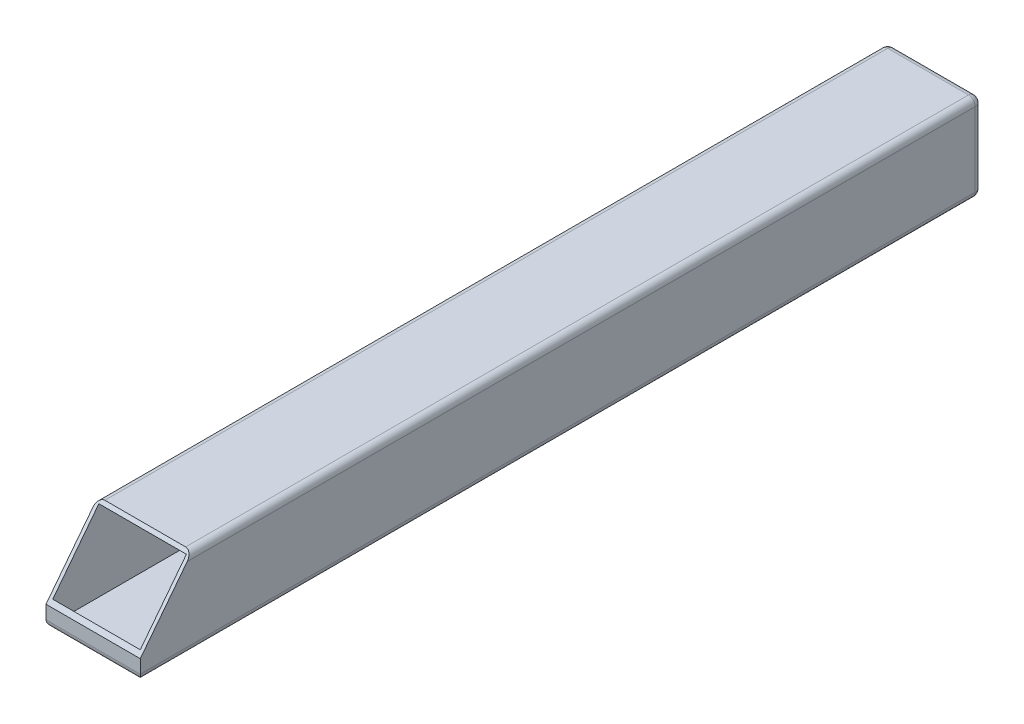
SolidWorks part; units mm, degrees
material "1060 Alloy"
ref_plane "Front Plane" through (0, 0, 0) normal (0, 0, 1) x (1, 0, 0)
ref_plane "Top Plane" through (0, 0, 0) normal (0, 1, 0) x (1, 0, 0)
ref_plane "Right Plane" through (0, 0, 0) normal (1, 0, 0) x (0, 0, -1)
sketch "Sketch1" plane through (0, 0, 0) normal (0, 1, 0) x (1, 0, 0)
  line L1 (0, 0) -> (177.8, 0)
  line L2 (0, 0) -> (0, 1587.5)
  line L3 (0, 1587.5) -> (177.8, 1587.5)
  line L4 (177.8, 0) -> (177.8, 1587.5)
  dimension "D1" = 1587.5
  dimension "D2" = 177.8
extrude "Boss-Extrude1" add sketch "Sketch1" along normal blind 165.1
sketch "Sketch2" plane through (177.8, 0, 0) normal (1, 0, 0) x (0, 0, -1)
  line L0 (0, 165.1) -> (98.3179, 165.1)
  line L1 (0, 165.1) -> (1587.5, 165.1) construction
  line L2 (98.3179, 165.1) -> (0, 38.1)
  line L4 (0, 38.1) -> (0, 165.1)
  line L5 (0, 165.1) -> (0, 0) construction
  point P5 (0, 28.2126)
  point P9 (98.3179, 165.1)
extrude "Cut-Extrude1" cut sketch "Sketch2" against normal up to surface (177.8 mm away) up to face at (0, 82.55, -793.75)
shell "Shell2" thickness 6.35
fillet "Fillet3" radius 12.7 9 edges at (88.9, 0, -1587.5) (88.9, 165.1, -1587.5) (177.8, 82.55, -1587.5) (0, 82.55, -1587.5) (0, 0, -793.75) (177.8, 0, -793.75) (88.9, 0, 0) (0, 165.1, -842.9089) (177.8, 165.1, -842.9089)
